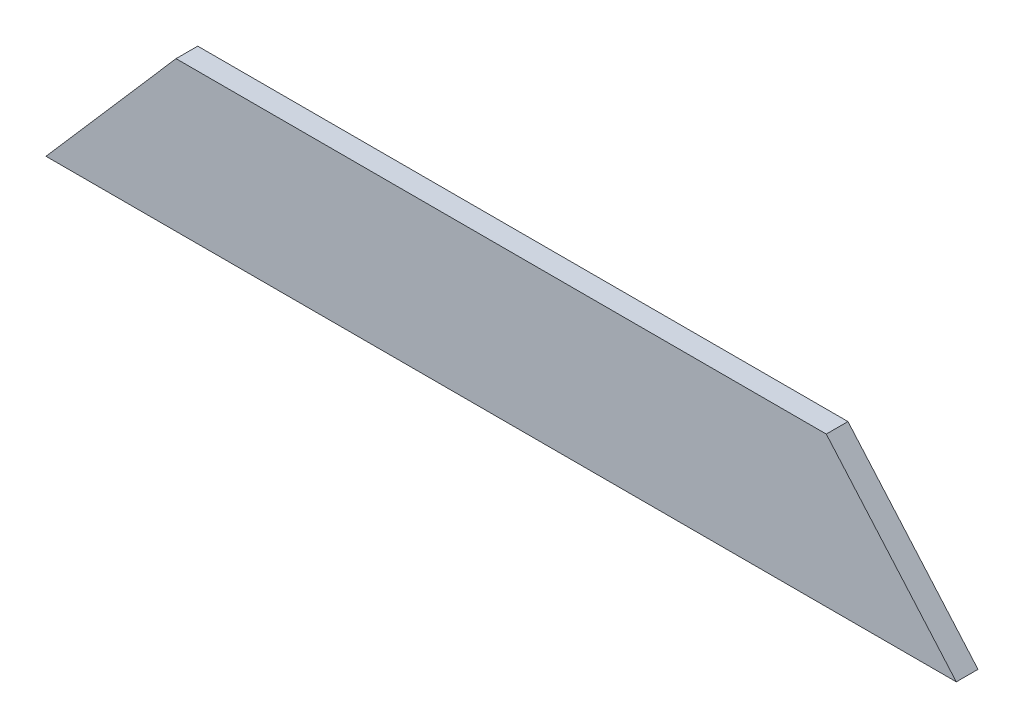
SolidWorks part; units mm, degrees
ref_plane "Ön Düzlem" through (0, 0, 0) normal (0, 0, 1) x (1, 0, 0)
ref_plane "Üst Düzlem" through (0, 0, 0) normal (0, 1, 0) x (1, 0, 0)
ref_plane "Sağ Düzlem" through (0, 0, 0) normal (1, 0, 0) x (0, 0, -1)
sketch "Çizim2" plane through (0, 0, 0) normal (0, 0, 1) x (1, 0, 0)
  line L0 (0, 0) -> (84, 0)
  line L1 (84, 0) -> (72, 13.8044)
  line L2 (72, 13.8044) -> (12, 13.8044)
  line L3 (12, 13.8044) -> (0, 0)
  point P3 (0, 0)
  point P6 (0, 0)
  point P7 (12.7964, 15.6966)
  dimension "D1" = 60
  dimension "D2" = 12
  dimension "D3" = 49
extrude "Yükseklik-Ekstrüzyon1" add sketch "Çizim2" along normal blind 2
